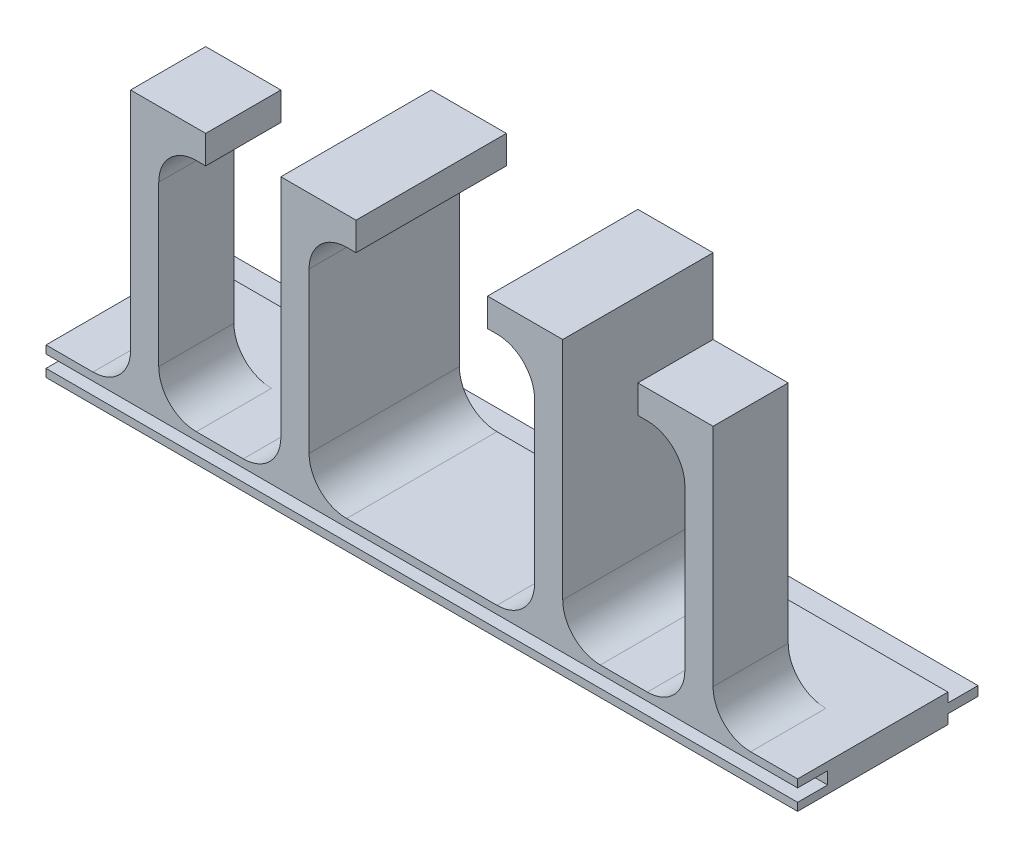
SolidWorks part; units mm, degrees
ref_plane "Front Plane" through (0, 0, 0) normal (0, 0, 1) x (1, 0, 0)
ref_plane "Top Plane" through (0, 0, 0) normal (0, 1, 0) x (1, 0, 0)
ref_plane "Right Plane" through (0, 0, 0) normal (1, 0, 0) x (0, 0, -1)
sketch "Sketch1" plane through (0, 0, 0) normal (0, 1, 0) x (1, 0, 0)
  line L1 (0, 0) -> (127, 0)
  line L2 (0, 0) -> (0, 25.4)
  line L3 (0, 25.4) -> (127, 25.4)
  line L4 (127, 0) -> (127, 25.4)
  dimension "D1" = 127
  dimension "D2" = 25.4
extrude "Boss-Extrude1" add sketch "Sketch1" along normal blind 4.7625
sketch "Sketch2" plane through (0, 4.7625, 0) normal (0, 1, 0) x (1, 0, 0)
  line L0 (0, 0) -> (127, 0) construction
  line L5 (39.6875, 0) -> (44.45, 0)
  line L6 (39.6875, 0) -> (39.6875, 25.4)
  line L7 (39.6875, 25.4) -> (44.45, 25.4)
  line L8 (44.45, 0) -> (44.45, 25.4)
  line L9 (127, 25.4) -> (0, 25.4) construction
  line L15 (19.05, 0) -> (14.2875, 0)
  line L16 (19.05, 0) -> (19.05, 12.7)
  line L17 (19.05, 12.7) -> (14.2875, 12.7)
  line L18 (14.2875, 0) -> (14.2875, 12.7)
  point P8 (63.5, 0)
  dimension "D1" = 19.05
  dimension "D2" = 4.7625
  dimension "D3" = 4.7625
  dimension "D4" = 12.7
  dimension "D5" = 44.45
extrude "Boss-Extrude2" add sketch "Sketch2" along normal blind 44.45
sketch "Sketch3" plane through (44.45, 0, 0) normal (1, 0, 0) x (0, 0, -1)
  line L0 (25.4, 49.2125) -> (25.4, 4.7625) construction
  line L1 (0, 49.2125) -> (25.4, 49.2125)
  line L2 (0, 49.2125) -> (0, 44.45)
  line L3 (0, 44.45) -> (25.4, 44.45)
  line L4 (25.4, 49.2125) -> (25.4, 44.45)
  dimension "D1" = 4.7625
extrude "Boss-Extrude3" add sketch "Sketch3" along normal blind 7.9375
sketch "Sketch4" plane through (19.05, 0, 0) normal (1, 0, 0) x (0, 0, -1)
  line L0 (12.7, 49.2125) -> (12.7, 4.7625) construction
  line L1 (0, 49.2125) -> (12.7, 49.2125)
  line L2 (0, 49.2125) -> (0, 44.45)
  line L3 (0, 44.45) -> (12.7, 44.45)
  line L4 (12.7, 49.2125) -> (12.7, 44.45)
  dimension "D1" = 4.7625
extrude "Boss-Extrude4" add sketch "Sketch4" along normal blind 7.9375
fillet "Fillet1" radius 6.35 6 edges at (44.45, 44.45, -12.7) (19.05, 44.45, -6.35) (14.2875, 4.7625, -6.35) (39.6875, 4.7625, -12.7) (44.45, 4.7625, -12.7) (19.05, 4.7625, -6.35)
ref_plane "Plane1" through (63.5, 0, 0) normal (1, 0, 0) x (0, 0, -1)
mirror "Mirror1" about plane through (63.5, 0, 0) normal (1, 0, 0) of "Fillet1", "Boss-Extrude4", "Boss-Extrude3", "Boss-Extrude2"
sketch "Sketch5" plane through (0, 0, 0) normal (0, 0, 1) x (1, 0, 0)
  line L0 (127, 4.7625) -> (127, 0) construction
  line L1 (127, 1.3335) -> (0, 1.3335)
  line L2 (127, 1.3335) -> (127, 3.429)
  line L3 (127, 3.429) -> (0, 3.429)
  line L4 (0, 1.3335) -> (0, 3.429)
  line L5 (0, 4.7625) -> (0, 0) construction
  dimension "D1" = 1.3335
  dimension "D2" = 2.0955
extrude "Cut-Extrude1" cut sketch "Sketch5" against normal blind 5.08
sketch "Sketch6" plane through (0, 0, -25.4) normal (0, 0, -1) x (-1, 0, 0)
  line L0 (-127, 4.7625) -> (-127, 0) construction
  line L1 (-127, 3.175) -> (0, 3.175)
  line L2 (-127, 3.175) -> (-127, 1.5875)
  line L3 (-127, 1.5875) -> (0, 1.5875)
  line L4 (0, 3.175) -> (0, 1.5875)
  line L5 (0, 4.7625) -> (0, 0) construction
  dimension "D1" = 1.5875
  dimension "D2" = 1.5875
extrude "Boss-Extrude5" add sketch "Sketch6" along normal blind 5.08
